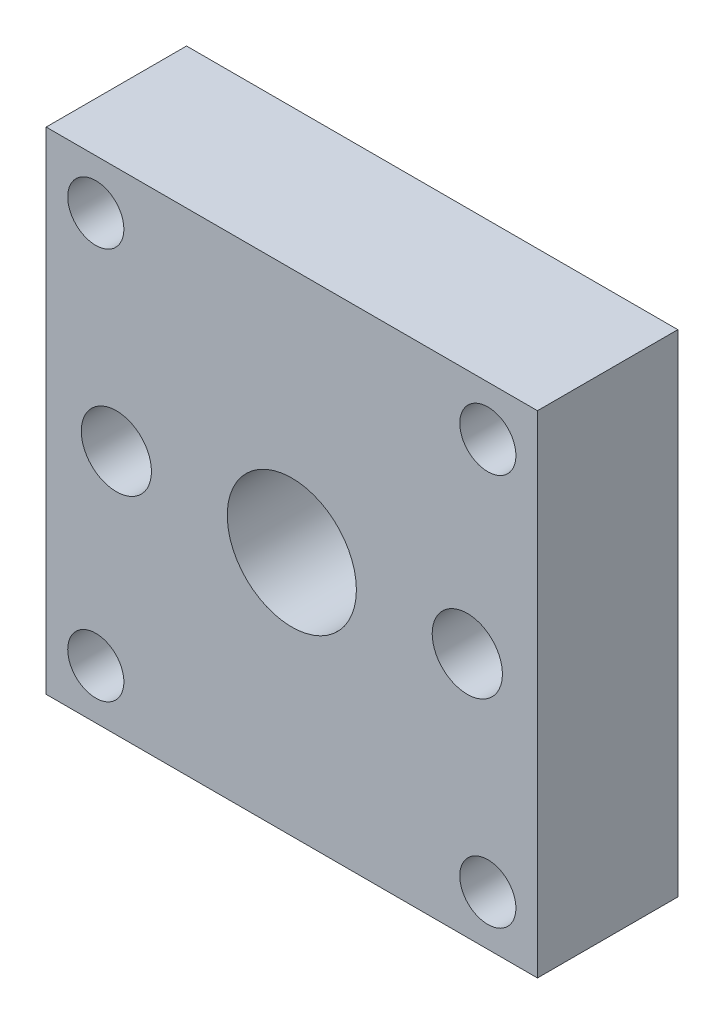
SolidWorks part; units mm, degrees
ref_plane "Front Plane" through (0, 0, 0) normal (0, 0, 1) x (1, 0, 0)
ref_plane "Top Plane" through (0, 0, 0) normal (0, 1, 0) x (1, 0, 0)
ref_plane "Right Plane" through (0, 0, 0) normal (1, 0, 0) x (0, 0, -1)
sketch "Sketch1" plane through (0, 0, 0) normal (0, 0, 1) x (1, 0, 0)
  line L0 (25.5319, -5.0588) -> (-9.4681, -5.0588) construction
  line L1 (-9.4681, 12.4412) -> (25.5319, 12.4412)
  line L2 (-9.4681, 12.4412) -> (-9.4681, -22.5588)
  line L3 (-9.4681, -22.5588) -> (25.5319, -22.5588)
  line L4 (25.5319, 12.4412) -> (25.5319, -22.5588)
  line L5 (-9.4681, 12.4412) -> (25.5319, -22.5588) construction
  line L6 (-9.4681, -22.5588) -> (25.5319, 12.4412) construction
  line L7 (8.0319, 12.4412) -> (8.0319, -22.5588) construction
  circle A0 centre (8.0319, -5.0588) radius 4.6
  circle A1 centre (21.9964, -19.0233) radius 2
  circle A2 centre (21.9964, 8.9057) radius 2
  circle A3 centre (-5.9325, -19.0233) radius 2
  circle A4 centre (-5.9325, 8.9057) radius 2
  circle A5 centre (-4.4681, -5.0588) radius 2.5
  circle A6 centre (20.5319, -5.0588) radius 2.5
  point P4 (8.0319, -5.0588)
  dimension "D3" = 9.2
  dimension "D4" = 4
  dimension "D6" = 5
  dimension "D1" = 35
  dimension "D2" = 35
  dimension "D5" = 5
extrude "Boss-Extrude1" add sketch "Sketch1" along normal blind 10
